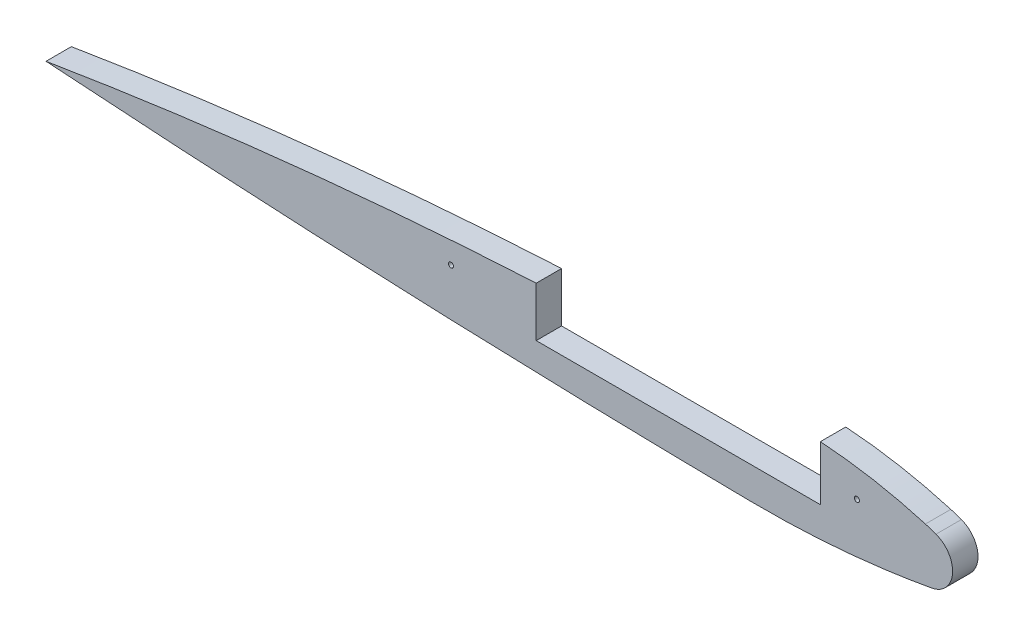
SolidWorks part; units mm, degrees
material "Carbon/Foam Panel"
ref_plane "Front Plane" through (0, 0, 0) normal (0, 0, 1) x (1, 0, 0)
ref_plane "Top Plane" through (0, 0, 0) normal (0, 1, 0) x (1, 0, 0)
ref_plane "Right Plane" through (0, 0, 0) normal (1, 0, 0) x (0, 0, -1)
sketch "Sketch1" plane through (0, 0, 0) normal (0, 0, 1) x (1, 0, 0)
  ellipse E1 centre (30.4917, -1212.2061) end of major axis (1372.9244, -1212.2061) minor radius 1244.6819 (36.9797, 32.4612) -> (-204.2943, 13.2914) ccw
  ellipse E3 centre (36.2563, -106.312) end of major axis (185.9298, -106.312) minor radius 138.7748 (81.5372, 25.9598) -> (36.9797, 32.4612) ccw
  ellipse E5 centre (65.7891, -20.0426) end of major axis (117.8436, -20.0426) minor radius 48.2641 (103.4339, 13.2914) -> (81.5372, 25.9598) ccw
  ellipse E7 centre (28.1769, 268.4704) end of major axis (313.5001, 268.4704) minor radius 264.5471 (24.2792, 3.948) -> (103.4339, 13.2914) ccw
  ellipse E9 centre (66.1797, 2847.5869) end of major axis (3464.1974, 2820.9695) minor radius 2843.9273 (-204.2943, 13.2914) -> (24.2792, 3.948) ccw
extrude "Boss-Extrude1" add sketch "Sketch1" along normal blind 6.35 contours E1 E9 E7 E5 E3
fillet "Fillet1" radius 6.35 1 edges at (103.4339, 13.2914, 3.175)
sketch "Sketch2" plane through (0, 0, 0) normal (0, 0, -1) x (-1, 0, 0)
  line L0 (46.0477, 25.527) -> (46.0477, 14.097) construction
  line L1 (10.4877, 25.527) -> (81.6077, 25.527)
  line L2 (10.4877, 25.527) -> (10.4877, 14.097)
  line L3 (10.4877, 14.097) -> (81.6077, 14.097)
  line L4 (81.6077, 25.527) -> (81.6077, 14.097)
  line L5 (81.6077, 19.812) -> (10.4877, 19.812) construction
  line L6 (13.0277, 25.527) -> (13.0277, 14.097) construction
  line L7 (3.4925, 0) -> (-3.4925, 0) construction
  dimension "D1" = 2.54
  dimension "D2" = 11.43
  dimension "D3" = 68.58
  dimension "D5" = 19.812
extrude "Cut-Extrude1" cut sketch "Sketch2" against normal through all
sketch "Sketch3" plane through (0, 0, 0) normal (0, 0, 1) x (1, 0, 0)
  line L0 (-10.4877, 25.527) -> (-10.4877, 14.097) construction
  line L2 (-102.9437, 19.812) -> (-1.3437, 19.812) construction
  circle A0 centre (-1.3437, 19.812) radius 0.635
  circle A1 centre (-102.9437, 19.812) radius 0.635
  point P7 (-10.4877, 19.812)
  dimension "D1" = 1.27
  dimension "D4" = 1.27
  dimension "D2" = 9.144
  dimension "D3" = 101.6
extrude "Cut-Extrude2" cut sketch "Sketch3" along normal through all
sketch "Sketch6" plane through (0, 0, 0) normal (0, 0, 1) x (1, 0, 0)
  ellipse E1 centre (-23.5091, -930.3417) end of major axis (1010.1641, -930.3417) minor radius 958.4051 (-18.5133, 28.0522) -> (-204.2943, 13.2914) ccw
  ellipse E3 centre (-19.0703, -78.8032) end of major axis (96.1783, -78.8032) minor radius 106.8566 (15.7959, 23.0461) -> (-18.5133, 28.0522) ccw
  ellipse E5 centre (3.6699, -12.3758) end of major axis (43.7519, -12.3758) minor radius 37.1633 (32.6564, 13.2914) -> (15.7959, 23.0461) ccw
  ellipse E7 centre (-25.2915, 209.7792) end of major axis (194.4074, 209.7792) minor radius 203.7012 (-28.2927, 6.097) -> (32.6564, 13.2914) ccw
  ellipse E9 centre (3.9707, 2195.6989) end of major axis (-2612.5029, 2216.1943) minor radius 2189.824 (-204.2943, 13.2914) -> (-28.2927, 6.097) ccw
extrude "Cut-Extrude4" cut sketch "Sketch6" along normal through all flip side to cut
fillet "Fillet3" radius 6.35 1 edges at (32.6564, 13.2914, 3.175)
sketch "Sketch8" plane through (0, 0, 0) normal (0, 0, 1) x (1, 0, 0)
  line L0 (-81.6077, 25.527) -> (-10.4877, 25.527) construction
  line L1 (-81.6077, 25.527) -> (-10.4877, 25.527)
  line L2 (-10.4877, 25.527) -> (-10.4877, 27.7567)
  line L3 (-81.6077, 25.527) -> (-81.6077, 26.5483)
  ellipse E0 centre (-23.5091, -930.3417) end of major axis (1010.1641, -930.3417) minor radius 958.4051 (-18.5133, 28.0522) -> (-204.2943, 13.2914) ccw construction
  ellipse E1 centre (-23.5091, -930.3417) end of major axis (1010.1641, -930.3417) minor radius 958.4051 (-18.5133, 28.0522) -> (-81.6077, 26.5483) ccw
  ellipse E2 centre (-19.0703, -78.8032) end of major axis (96.1783, -78.8032) minor radius 106.8566 (15.7959, 23.0461) -> (-18.5133, 28.0522) ccw construction
  ellipse E3 centre (-19.0703, -78.8032) end of major axis (96.1783, -78.8032) minor radius 106.8566 (-10.4877, 27.7567) -> (-18.5133, 28.0522) ccw
extrude "Cut-Extrude5" cut sketch "Sketch8" along normal through all
equation "\"D4@Sketch3\"=\"D1@Sketch3\""
